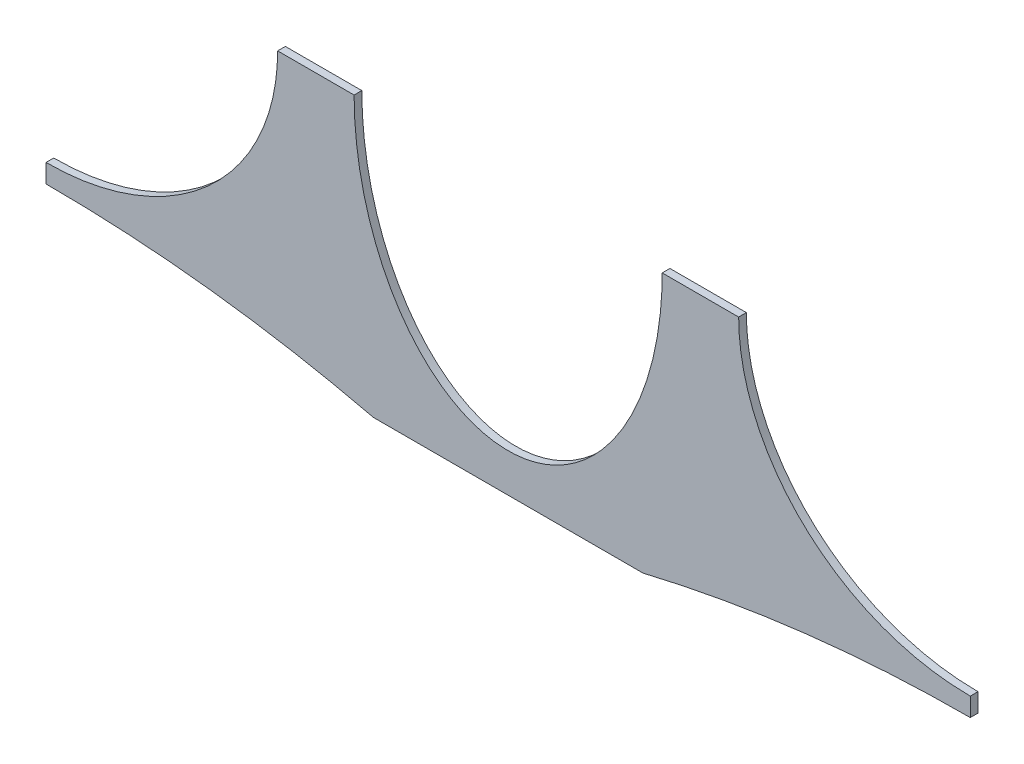
SolidWorks part; units mm, degrees
ref_plane "Front Plane" through (0, 0, 0) normal (0, 0, 1) x (1, 0, 0)
ref_plane "Top Plane" through (0, 0, 0) normal (0, 1, 0) x (1, 0, 0)
ref_plane "Right Plane" through (0, 0, 0) normal (1, 0, 0) x (0, 0, -1)
sketch "Sketch1" plane through (0, 0, 0) normal (0, 0, 1) x (1, 0, 0)
  line L0 (-14.2584, 0) -> (19.86, 0) construction
  line L1 (0, 0) -> (0, 23.1598) construction
  line L2 (-33.4641, 76.2) -> (17.6005, 76.2) construction
  line L3 (-152.4, 0) -> (-152.4, 164.6454) construction
  line L4 (152.4, 0) -> (152.4, 115.8532) construction
  line L5 (-76.0134, 76.2) -> (-50.8, 76.2)
  line L6 (50.8, 76.2) -> (76.0134, 76.2)
  line L7 (-44.45, -12.7) -> (44.45, -12.7)
  line L8 (152.4, 6.1369) -> (152.4, 0)
  line L9 (-152.4, 6.1369) -> (-152.4, 0)
  arc A0 (-44.45, -12.7) -> (-152.4, 0) centre (-152.4, -465.1375) ccw
  arc A1 (152.4, 0) -> (44.45, -12.7) centre (152.4, -465.1375) ccw
  ellipse E0 centre (0, 76.2) end of major axis (0, 152.4) minor radius 50.8 (-50.8, 76.2) -> (50.8, 76.2) ccw
  ellipse E1 centre (-152.4, 76.2) end of major axis (-76.0134, 76.2) minor radius 70.0631 (-152.4, 6.1369) -> (-76.0134, 76.2) ccw
  ellipse E2 centre (152.4, 76.2) end of major axis (76.0134, 76.2) minor radius 70.0631 (152.4, 6.1369) -> (76.0134, 76.2) cw
  dimension "D4" = 76.3866
  dimension "D5" = 70.0631
  dimension "D1" = 76.2
  dimension "D2" = 152.4
  dimension "D3" = 304.8
  dimension "D6" = 50.8
  dimension "D7" = 44.45
  dimension "D8" = 88.9
  dimension "D9" = 12.7
extrude "Boss-Extrude1" add sketch "Sketch1" along normal blind 2.54 contours E1 L5 E0 L6 E2 L8 A1 L7 A0 L9
